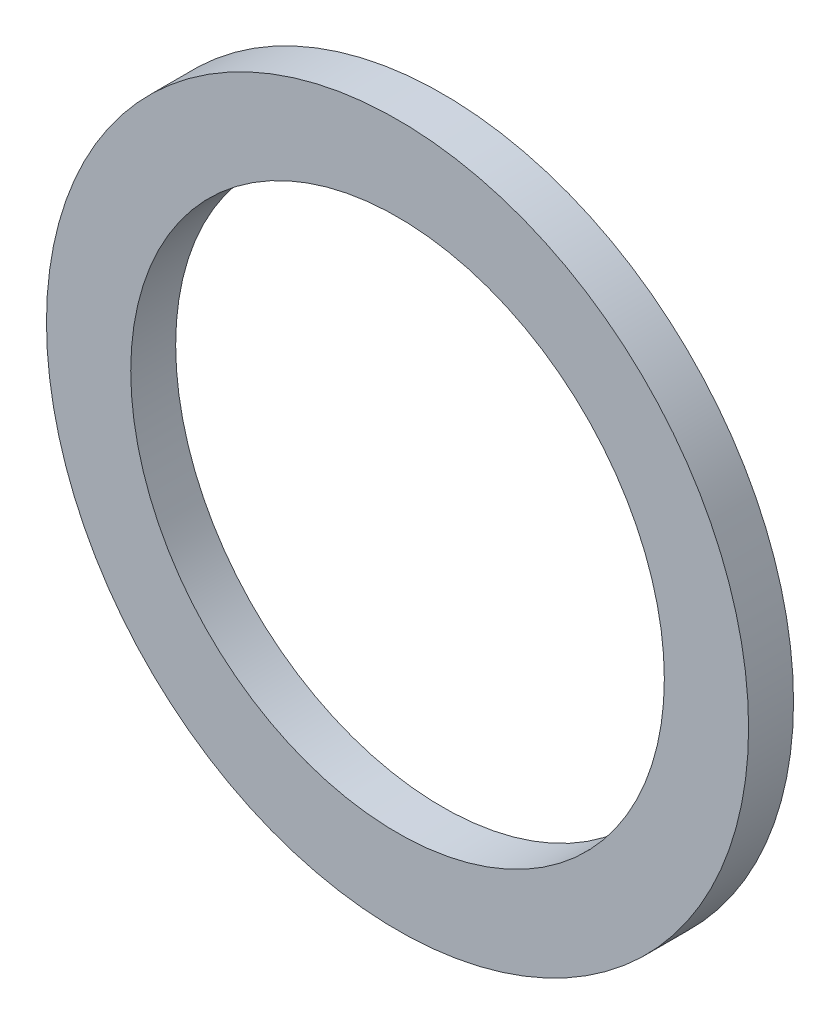
SolidWorks part; units mm, degrees
material "Alloy Steel (SS)"
ref_plane "Front" through (0, 0, 0) normal (0, 0, 1) x (1, 0, 0)
ref_plane "Top" through (0, 0, 0) normal (0, 1, 0) x (1, 0, 0)
ref_plane "Right" through (0, 0, 0) normal (1, 0, 0) x (0, 0, -1)
sketch "Sketch2" plane through (0, 0, 0) normal (0, 0, 1) x (1, 0, 0)
  circle A0 centre (0, 0) radius 2.413
  circle A1 centre (0, 0) radius 3.175
  dimension "D1" = 4.826
  dimension "D2" = 6.35
extrude "Boss-Extrude1" add sketch "Sketch2" along normal blind 0.4064 contours A1
